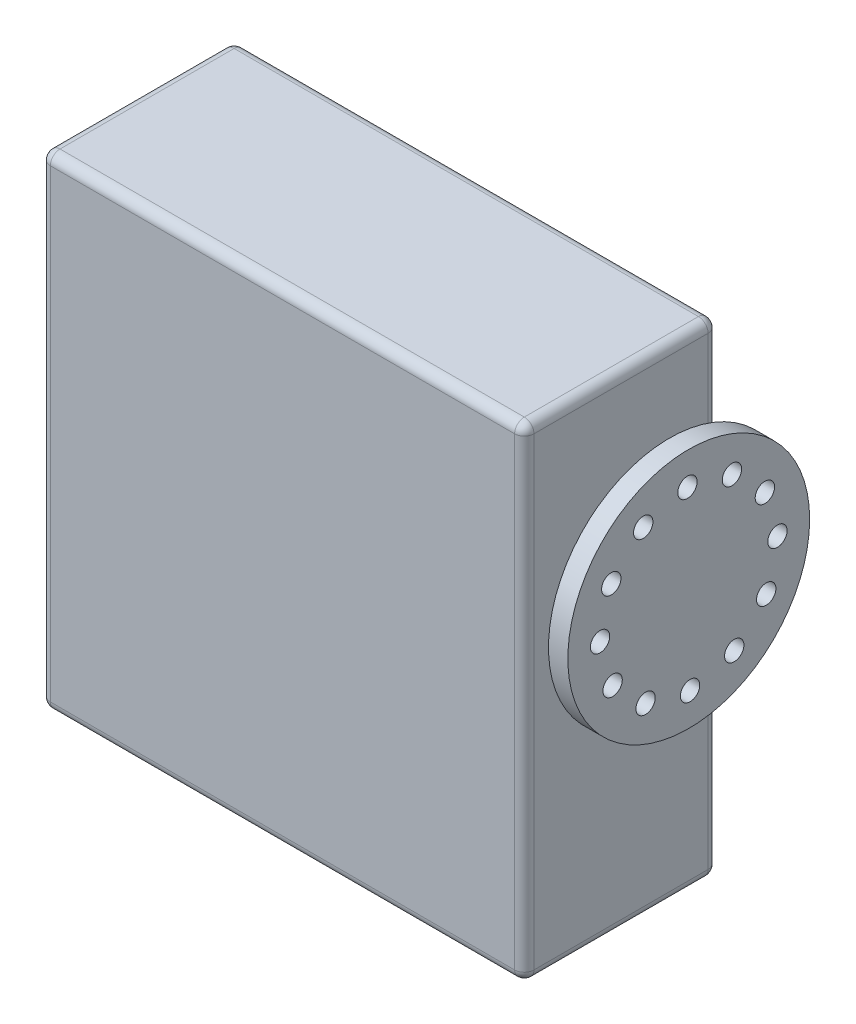
SolidWorks part; units mm, degrees
ref_plane "Front Plane" through (0, 0, 0) normal (0, 0, 1) x (1, 0, 0)
ref_plane "Top Plane" through (0, 0, 0) normal (0, 1, 0) x (1, 0, 0)
ref_plane "Right Plane" through (0, 0, 0) normal (1, 0, 0) x (0, 0, -1)
sketch "Sketch1" plane through (0, 0, 0) normal (0, 0, 1) x (1, 0, 0)
  line L1 (0, 0) -> (50, 0)
  line L2 (0, 0) -> (0, 50)
  line L3 (0, 50) -> (50, 50)
  line L4 (50, 0) -> (50, 50)
  dimension "D1" = 50
  dimension "D2" = 50
extrude "Boss-Extrude1" add sketch "Sketch1" along normal blind 20
sketch "Sketch2" plane through (50, 0, 0) normal (1, 0, 0) x (0, 0, -1)
  line L0 (-10, 50) -> (-10, 0) construction
  line L1 (-20, 50) -> (0, 50) construction
  line L2 (-20, 0) -> (0, 0) construction
  circle A0 centre (-10, 34.1133) radius 2.5
  dimension "D1" = 5
extrude "Boss-Extrude2" add sketch "Sketch2" along normal blind 5
sketch "Sketch3" plane through (55, 0, 0) normal (1, 0, 0) x (0, 0, -1)
  circle A0 centre (-10, 34.1133) radius 12.5
  dimension "D1" = 25
extrude "Boss-Extrude3" add sketch "Sketch3" along normal blind 2
fillet "Fillet1" radius 1 12 edges at (50, 25, 20) (0, 25, 20) (0, 0, 10) (25, 0, 20) (50, 0, 10) (25, 0, 0) (50, 25, 0) (0, 25, 0) (50, 50, 10) (25, 50, 20) (0, 50, 10) (25, 50, 0)
hole_wizard "Ø2.0mm Dowel Hole1" positions "Sketch5" profile "Sketch4" hole size "Ø2.0" standard "ANSI Metric"
sketch "Sketch5" plane through (57, 0, 0) normal (1, 0, 0) x (0, 0, -1)
  point P0 (-0.8316, 34.2517)
sketch "Sketch4" plane through (57, 34.2517, 0.8316) normal (0, 1, 0) x (0, 0, -1)
  line L0 (0, 0) -> (0, 2.6009)
  line L1 (0, 2.6009) -> (1, 2)
  line L2 (1, 2) -> (1, 0)
  line L5 (1, 0) -> (0, 0)
  line L10 (0, 2.6009) -> (-1, 2) construction
  line L11 (0, -6.35) -> (0, 107.95) construction
  dimension "Hole Dia." = 2
  dimension "Hole Depth" = 2
  dimension "Drill Angle" = 118
pattern_circular "CirPattern1" count 12 over 360 about axis through (0, 34.1133, 10) along (1, 0, 0) of "Ø2.0mm Dowel Hole1"
sketch "Sketch6" plane through (0, 50, 0) normal (0, 1, 0) x (1, 0, 0)
  line L0 (49, -10) -> (1, -10) construction
  line L1 (49, -19) -> (49, -1) construction
  line L2 (1, -1) -> (1, -19) construction
